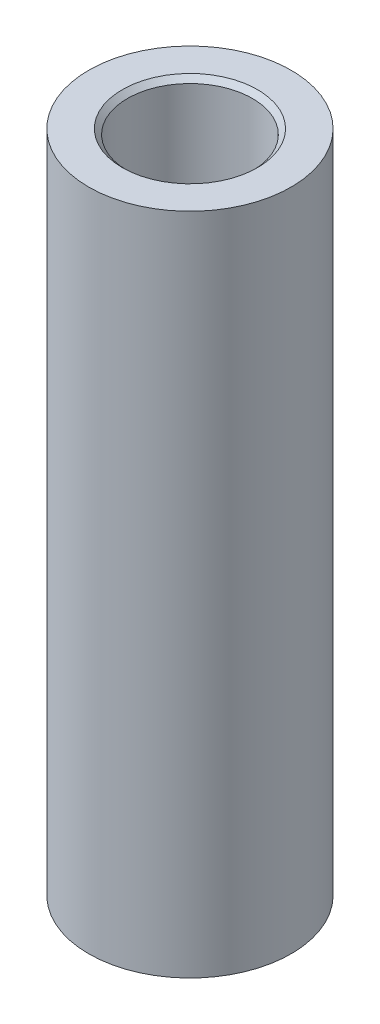
SolidWorks part; units mm, degrees
ref_plane "Front Plane" through (0, 0, 0) normal (0, 0, 1) x (1, 0, 0)
ref_plane "Top Plane" through (0, 0, 0) normal (0, 1, 0) x (1, 0, 0)
ref_plane "Right Plane" through (0, 0, 0) normal (1, 0, 0) x (0, 0, -1)
sketch "Sketch1" plane through (0, 0, 0) normal (0, 1, 0) x (1, 0, 0)
  circle A0 centre (0, 0) radius 7.9375
extrude "Boss-Extrude1" add sketch "Sketch1" along normal blind 52.07
hole_wizard "W (0.386) Diameter Hole1" positions "Sketch3" profile "Sketch4" hole size "W" standard "ANSI Inch" end condition through all
sketch "Sketch3" plane through (0, 52.07, 0) normal (0, 1, 0) x (1, 0, 0)
  point P0 (0, 0)
sketch "Sketch4" plane through (0, 52.07, 0) normal (1, 0, 0) x (0, 0, 1)
  line L0 (0, 0) -> (0, 52.07)
  line L1 (0, 52.07) -> (4.9022, 52.07)
  line L2 (4.9022, 52.07) -> (4.9022, 0)
  line L5 (4.9022, 0) -> (0, 0)
  line L11 (0, -6.35) -> (0, 107.95) construction
  dimension "Thru Hole Dia." = 9.8044
  dimension "Thru Hole Depth" = 52.07
chamfer "Chamfer1" distance 0.4 angle 45 2 edges at (0, 0, 4.9022) (0, 52.07, 4.9022)
